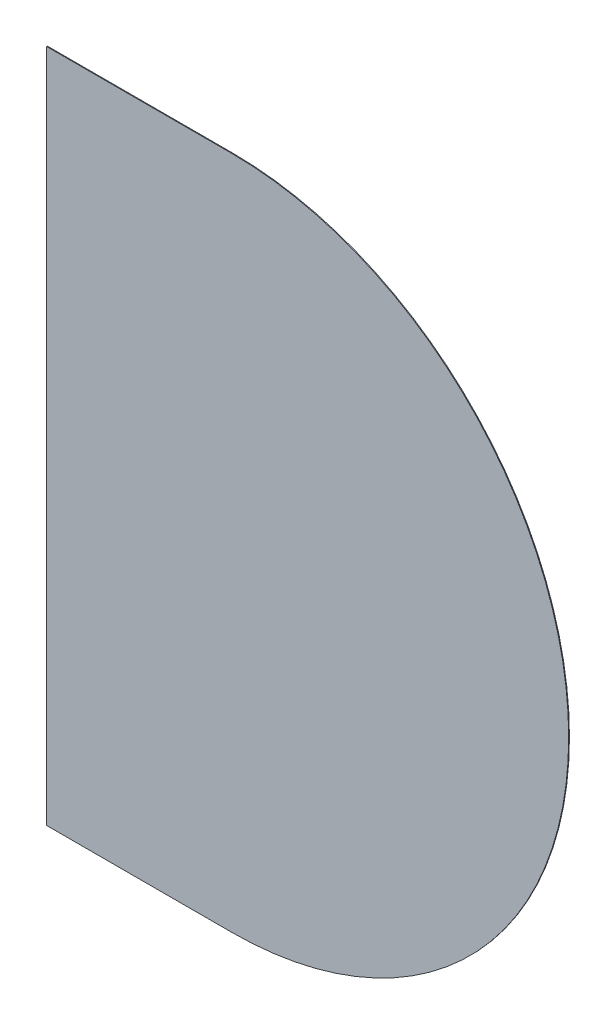
SolidWorks part; units mm, degrees
ref_plane "Front Plane" through (0, 0, 0) normal (0, 0, 1) x (1, 0, 0)
ref_plane "Top Plane" through (0, 0, 0) normal (0, 1, 0) x (1, 0, 0)
ref_plane "Right Plane" through (0, 0, 0) normal (1, 0, 0) x (0, 0, -1)
sketch "Sketch1" plane through (0, 0, 0) normal (0, 0, 1) x (1, 0, 0)
  line L1 (0, 0) -> (485, 0)
  line L2 (0, 0) -> (0, 1770)
  line L3 (0, 1770) -> (485, 1770)
  line L4 (485, 0) -> (485, 1770) construction
  arc A0 (485, 1770) -> (485, 0) centre (485, 885) cw
  dimension "D1" = 485
  dimension "D2" = 1770
extrude "Boss-Extrude1" add sketch "Sketch1" along normal blind 2
